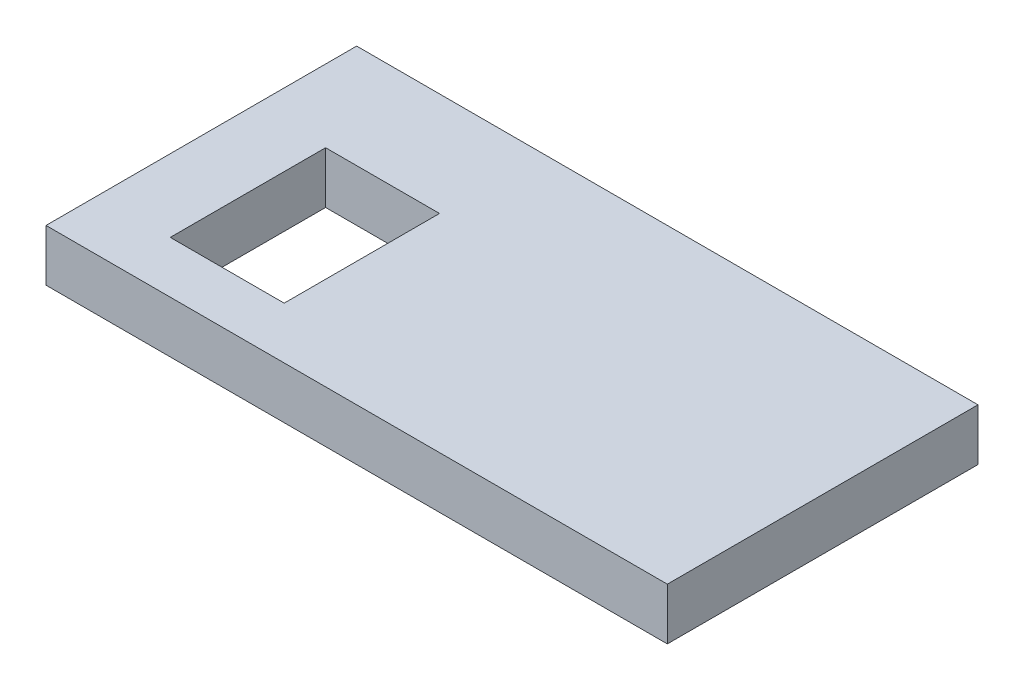
SolidWorks part; units mm, degrees
material "Kiefer"
ref_plane "Ebene vorne" through (0, 0, 0) normal (0, 0, 1) x (1, 0, 0)
ref_plane "Ebene oben" through (0, 0, 0) normal (0, 1, 0) x (1, 0, 0)
ref_plane "Ebene rechts" through (0, 0, 0) normal (1, 0, 0) x (0, 0, -1)
sketch "Skizze1" plane through (0, 0, 0) normal (0, 1, 0) x (1, 0, 0)
  line L1 (-60, 25) -> (60, 25)
  line L2 (-60, 25) -> (-60, -25)
  line L3 (-60, -25) -> (60, -25)
  line L4 (60, 25) -> (60, -25)
  line L5 (-60, 25) -> (60, -25) construction
  line L6 (-60, -25) -> (60, 25) construction
  point P0 (0, 0)
  dimension "D1" = 50
  dimension "D2" = 120
extrude "Aufsatz-Linear austragen1" add sketch "Skizze1" along normal blind 10
sketch "Skizze3" plane through (0, 10, 0) normal (0, 1, 0) x (1, 0, 0)
  line L0 (-60, -25) -> (60, -25) construction
  line L1 (60, -25) -> (60, 25) construction
  line L4 (-10, 25) -> (-10, -25) construction
  line L8 (-10, -25) -> (-60, -25) construction
  line L9 (-10, -25) -> (-10, 25) construction
  line L10 (-10, 25) -> (-60, 25) construction
  line L11 (-60, -25) -> (-60, 25) construction
  line L12 (-10, -25) -> (-60, 25) construction
  line L13 (-10, 25) -> (-60, -25) construction
  line L14 (-46, 15) -> (-24, 15)
  line L15 (-46, 15) -> (-46, -15)
  line L16 (-46, -15) -> (-24, -15)
  line L17 (-24, 15) -> (-24, -15)
  line L18 (-46, 15) -> (-24, -15) construction
  line L19 (-46, -15) -> (-24, 15) construction
  point P12 (-35, 0)
  point P14 (-35, 0)
  dimension "D1" = 70
  dimension "D3" = 22
  dimension "D4" = 30
extrude "Schnitt-Linear austragen1" cut sketch "Skizze3" against normal through all
sketch "Skizze4" plane through (0, 10, 0) normal (0, 1, 0) x (1, 0, 0)
  line L0 (-60, 25) -> (-60, -25) construction
  line L1 (60, 25) -> (-60, 25)
  line L2 (60, 25) -> (60, 35)
  line L3 (60, 35) -> (-60, 35)
  line L4 (-60, 25) -> (-60, 35)
  line L5 (60, 25) -> (-60, 35) construction
  line L6 (60, 35) -> (-60, 25) construction
  point P4 (0, 30)
  dimension "D1" = 10
extrude "Aufsatz-Linear austragen2" add sketch "Skizze4" against normal up to surface (10 mm away) up to face at (-35, 0, 0)
